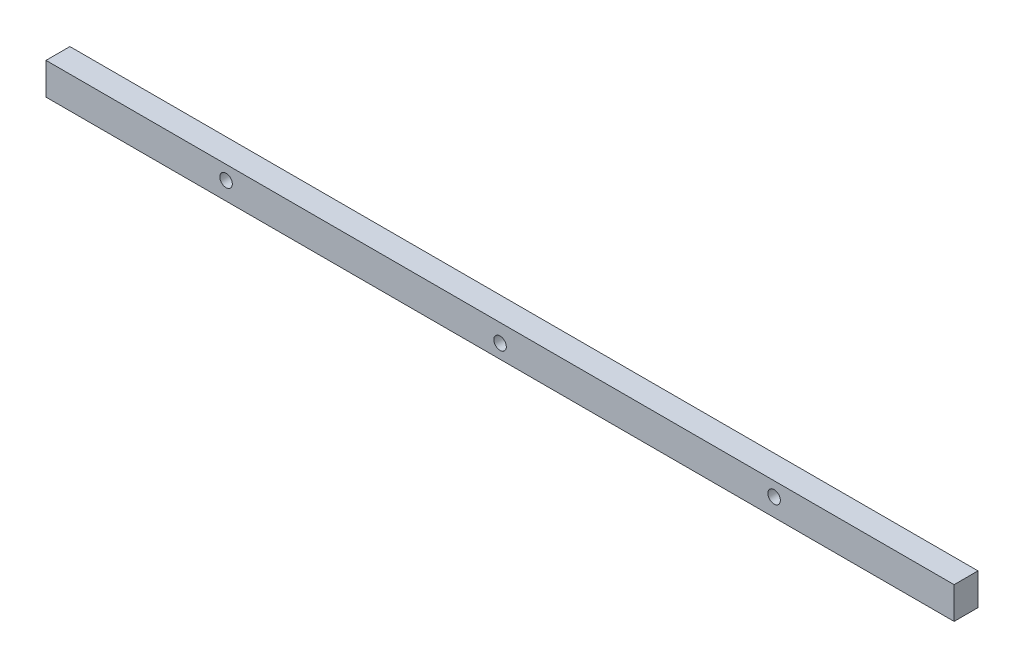
SolidWorks part; units mm, degrees
material "Polyethylene Cross-Linked"
ref_plane "Front Plane" through (0, 0, 0) normal (0, 0, 1) x (1, 0, 0)
ref_plane "Top Plane" through (0, 0, 0) normal (0, 1, 0) x (1, 0, 0)
ref_plane "Right Plane" through (0, 0, 0) normal (1, 0, 0) x (0, 0, -1)
sketch "Sketch1" plane through (0, 0, 0) normal (0, 0, 1) x (1, 0, 0)
  line L0 (180.975, 12.7) -> (180.975, 7.1437) construction
  line L1 (0, 0) -> (361.95, 0)
  line L2 (0, 0) -> (0, 12.7)
  line L3 (0, 12.7) -> (361.95, 12.7)
  line L4 (361.95, 0) -> (361.95, 12.7)
  line L5 (180.975, 7.1437) -> (180.975, 5.5563) construction
  line L6 (71.755, 7.1437) -> (290.195, 7.1438) construction
  circle A1 centre (180.975, 5.5563) radius 2.5
  circle A2 centre (71.755, 7.1437) radius 2.5
  circle A3 centre (290.195, 7.1438) radius 2.5
  point P12 (180.975, 7.1437)
  point P14 (72.7304, 7.1437)
  point P16 (289.2065, 7.1438)
  dimension "D5" = 218.44
  dimension "D1" = 12.7
  dimension "D2" = 361.95
  dimension "D3" = 5.5562
  dimension "D4" = 1.5875
extrude "Boss-Extrude1" add sketch "Sketch1" along normal blind 9.525
